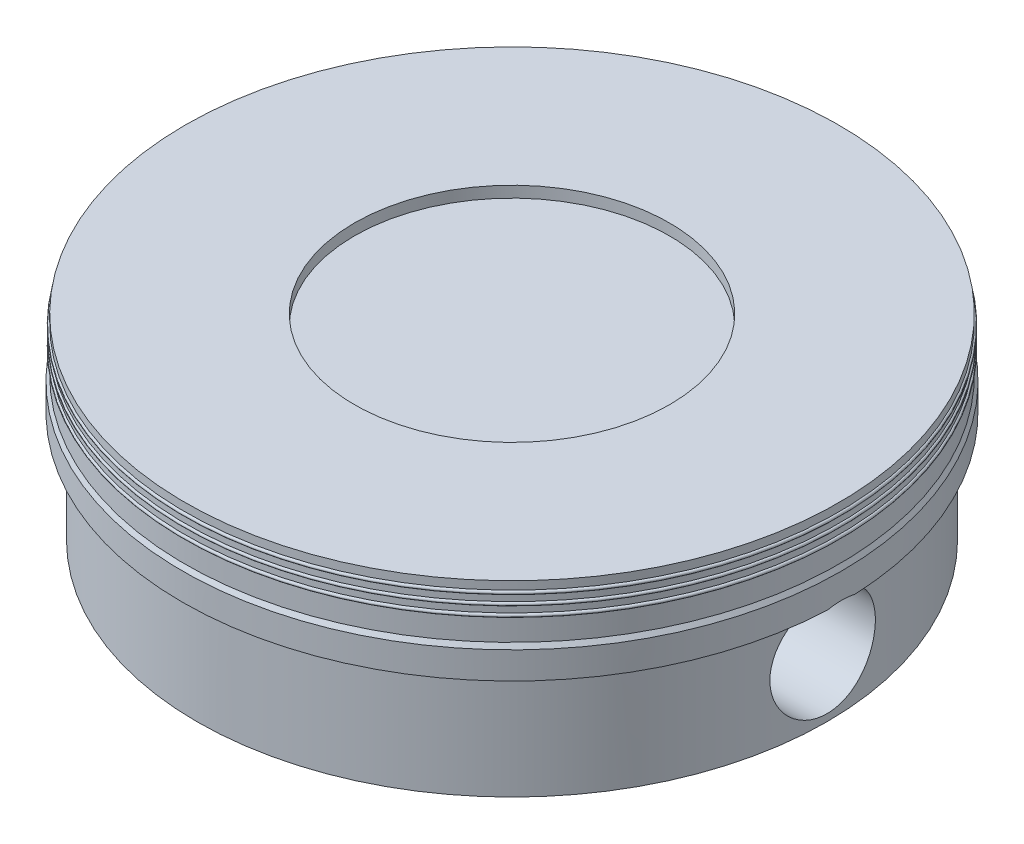
SolidWorks part; units mm, degrees
ref_plane "Front Plane" through (0, 0, 0) normal (0, 0, 1) x (1, 0, 0)
ref_plane "Top Plane" through (0, 0, 0) normal (0, 1, 0) x (1, 0, 0)
ref_plane "Right Plane" through (0, 0, 0) normal (1, 0, 0) x (0, 0, -1)
sketch "Sketch1" plane through (0, 0, 0) normal (0, 0, 1) x (1, 0, 0)
  line L0 (0, 3) -> (0, 0) construction
  line L1 (0, 0) -> (5, 0) construction
  line L2 (4.78, 0) -> (3.43, 0)
  line L3 (3.43, 0) -> (3.43, 1.93)
  line L4 (3.43, 1.93) -> (4.2, 1.93)
  line L5 (4.2, 1.93) -> (4.2, 2.33)
  line L6 (4.2, 2.33) -> (0, 2.33)
  line L7 (0, 2.33) -> (0, 2.8)
  line L8 (0, 2.8) -> (2.39, 2.8)
  line L9 (2.39, 2.8) -> (2.39, 2.97)
  line L10 (2.39, 2.97) -> (4.96, 2.97)
  line L11 (4.96, 2.97) -> (4.96, 2.8465)
  line L12 (4.96, 2.16) -> (5, 2.09)
  line L13 (5, 2.09) -> (5, 1.68)
  line L14 (5, 1.68) -> (4.78, 1.68)
  line L15 (4.78, 1.68) -> (4.78, 0)
  line L16 (4.96, 2.7935) -> (4.96, 2.6952)
  line L17 (4.96, 2.6448) -> (4.96, 2.5465)
  line L18 (4.96, 2.4935) -> (4.96, 2.16)
  arc A0 (4.96, 2.7935) -> (4.96, 2.8465) centre (4.96, 2.82) ccw
  arc A1 (4.96, 2.6448) -> (4.96, 2.6952) centre (4.96, 2.67) ccw
  arc A2 (4.96, 2.4935) -> (4.96, 2.5465) centre (4.96, 2.52) ccw
  point P22 (0, 0)
  dimension "D15" = 0.15
  dimension "D1" = 5
  dimension "D2" = 3
  dimension "D3" = 4.96
  dimension "D4" = 0.04
  dimension "D5" = 0.22
  dimension "D6" = 1.68
  dimension "D7" = 1.35
  dimension "D8" = 1.93
  dimension "D9" = 0.4
  dimension "D10" = 2.57
  dimension "D11" = 0.47
  dimension "D12" = 0.17
  dimension "D13" = 4.2
  dimension "D14" = 0.15
  dimension "D16" = 0.15
  dimension "D17" = 0.15
  dimension "D18" = 0.41
  dimension "D19" = 0.07
revolve "Revolve1" add sketch "Sketch1" angle 360 about L0
sketch "Sketch3" plane through (0, 0, 0) normal (0, -1, 0) x (1, 0, 0)
  line L1 (-1.75, 0) -> (-3.43, 0) construction
  line L2 (-1.75, 2.95) -> (-1.75, -2.95)
  line L3 (1.75, 2.95) -> (1.75, -2.95)
  circle A0 centre (0, 0) radius 3.43 construction
  arc A1 (-1.75, 2.95) -> (-1.75, -2.95) centre (0, 0) ccw
  arc A2 (1.75, -2.95) -> (1.75, 2.95) centre (0, 0) ccw
  dimension "D1" = 3.5
extrude "Boss-Extrude1" add sketch "Sketch3" against normal up to next
sketch "Sketch4" plane through (0, 0, 0) normal (1, 0, 0) x (0, 0, -1)
  circle A0 centre (0, 0.9065) radius 0.8
  point P2 (0, 0)
  dimension "D1" = 1.6
  dimension "D2" = 0.9065
extrude "Cut-Extrude1" cut sketch "Sketch4" against normal through all both and the other way through all
